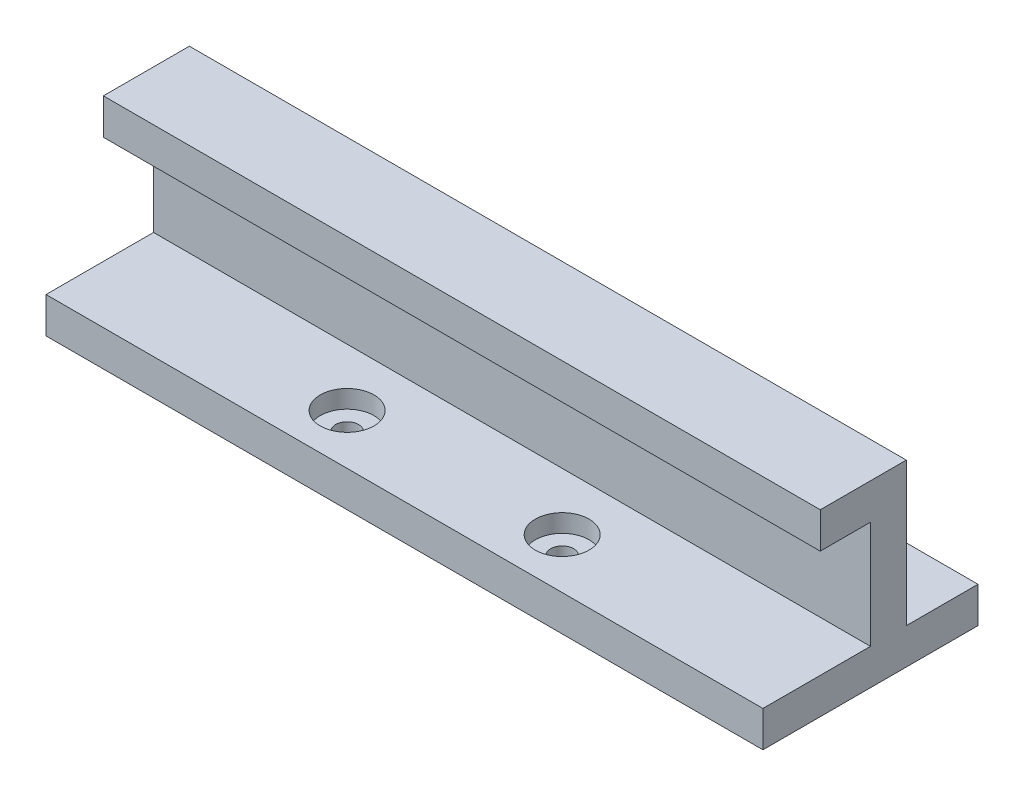
SolidWorks part; units mm, degrees
ref_plane "Front Plane" through (0, 0, 0) normal (0, 0, 1) x (1, 0, 0)
ref_plane "Top Plane" through (0, 0, 0) normal (0, 1, 0) x (1, 0, 0)
ref_plane "Right Plane" through (0, 0, 0) normal (1, 0, 0) x (0, 0, -1)
sketch "Sketch1" plane through (0, 0, 0) normal (0, 1, 0) x (1, 0, 0)
  line L0 (50, 20) -> (50, 0) construction
  line L1 (0, 0) -> (100, 0)
  line L2 (0, 0) -> (0, 20)
  line L3 (0, 20) -> (100, 20)
  line L4 (100, 0) -> (100, 20)
  circle A0 centre (35, 7) radius 1.6
  circle A1 centre (65, 7) radius 1.6
  dimension "D3" = 3.2
  dimension "D4" = 3.2
  dimension "D1" = 20
  dimension "D2" = 100
  dimension "D5" = 7
  dimension "D6" = 7
  dimension "D7" = 30
  dimension "D8" = 15
extrude "Extrude-Base" add sketch "Sketch1" along normal blind 5
sketch "Sketch2" plane through (0, 5, 0) normal (0, 1, 0) x (1, 0, 0)
  line L0 (100, 0) -> (100, 20) construction
  line L1 (0, 20) -> (100, 20)
  line L2 (0, 20) -> (0, 15)
  line L3 (0, 15) -> (100, 15)
  line L4 (100, 20) -> (100, 15)
  dimension "D1" = 5
extrude "Extrude-Vertical clamp" add sketch "Sketch2" along normal blind 20
sketch "Sketch3" plane through (0, 0, -15) normal (0, 0, 1) x (1, 0, 0)
  line L0 (100, 25) -> (100, 5) construction
  line L1 (0, 25) -> (100, 25)
  line L2 (0, 25) -> (0, 20)
  line L3 (0, 20) -> (100, 20)
  line L4 (100, 25) -> (100, 20)
  dimension "D1" = 5
extrude "Extrude-Clamp Roof" add sketch "Sketch3" along normal blind 7
sketch "Sketch5" plane through (0, 0, 0) normal (0, 1, 0) x (1, 0, 0)
  line L0 (100, 20) -> (100, 30)
  line L1 (100, 30) -> (0, 30)
  line L2 (0, 30) -> (0, 20)
  line L3 (0, 20) -> (100, 20)
  line L4 (50, 20) -> (50, 30) construction
  circle A0 centre (70, 25) radius 1.6
  circle A1 centre (30, 25) radius 1.6
  dimension "D2" = 20
  dimension "D6" = 3.2
  dimension "D7" = 3.2
  dimension "D1" = 10
  dimension "D3" = 20
  dimension "D4" = 5
  dimension "D5" = 5
extrude "Boss-Extrude4" add sketch "Sketch5" along normal blind 5
sketch "Sketch4" plane through (0, 5, 0) normal (0, 1, 0) x (1, 0, 0)
  circle A0 centre (35, 7) radius 3.75
  circle A1 centre (65, 7) radius 3.75
  circle A2 centre (35, 7) radius 1.6 construction
  circle A3 centre (65, 7) radius 1.6 construction
  circle A4 centre (30, 25) radius 3.75
  circle A5 centre (70, 25) radius 3.75
  dimension "D1" = 7.5
  dimension "D2" = 7.5
  dimension "D3" = 7.5
  dimension "D4" = 7.5
extrude "Cut-Extrude1" cut sketch "Sketch4" against normal blind 2.5
equation "\"screwInset\"=7.5"
equation "\"D1@Sketch4\"=\"screwInset\""
equation "\"D2@Sketch4\"=\"screwInset\""
equation "\"D3@Sketch4\"=\"screwInset\""
equation "\"D4@Sketch4\"=\"screwInset\""
